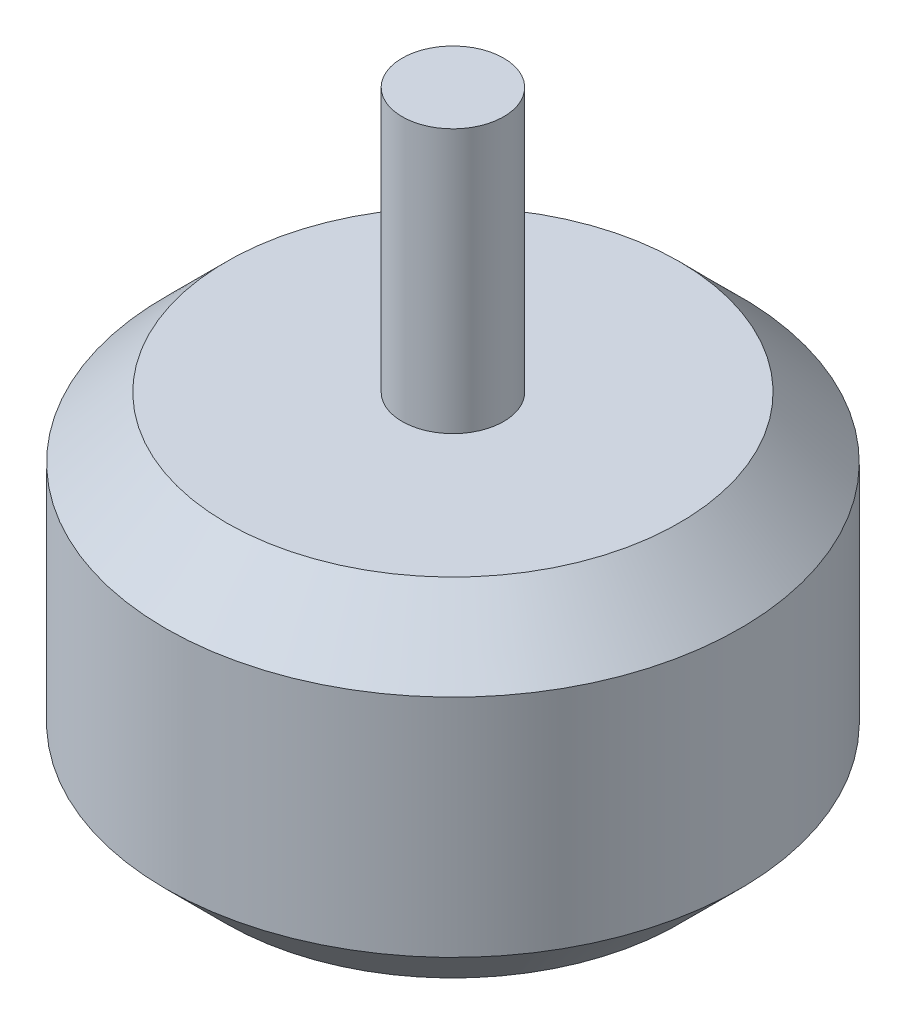
SolidWorks part; units mm, degrees
material "自定义塑料"
ref_plane "前视基准面" through (0, 0, 0) normal (0, 0, 1) x (1, 0, 0)
ref_plane "上视基准面" through (0, 0, 0) normal (0, 1, 0) x (1, 0, 0)
ref_plane "右视基准面" through (0, 0, 0) normal (1, 0, 0) x (0, 0, -1)
sketch "草图1" plane through (0, 0, 0) normal (0, 1, 0) x (1, 0, 0)
  circle A0 centre (0, 0) radius 14.15
  dimension "D1" = 28.3
extrude "凸台-拉伸1" add sketch "草图1" along normal blind 17.1
sketch "草图2" plane through (0, 17.1, 0) normal (0, 1, 0) x (1, 0, 0)
  circle A0 centre (0, 0) radius 2.5
  dimension "D1" = 5
extrude "凸台-拉伸2" add sketch "草图2" along normal blind 13
chamfer "倒角1" distance 3 angle 45 2 edges at (0, 0, 14.15) (0, 17.1, 14.15)
sketch "草图3" plane through (0, 0, 0) normal (0, -1, 0) x (1, 0, 0)
  line L0 (-1000, 0) -> (49000, 0) construction
  line L1 (0, -1000) -> (0, 49000) construction
  circle A0 centre (-8, 0) radius 1.5
  circle A1 centre (0, 8) radius 1.5
  circle A2 centre (8, 0) radius 1.5
  circle A3 centre (0, -8) radius 1.5
  dimension "D1" = 3
  dimension "D2" = 3
  dimension "D3" = 8
  dimension "D4" = 8
extrude "切除-拉伸1" cut sketch "草图3" against normal blind 4
sketch "草图4" plane through (0, 0, 0) normal (0, -1, 0) x (1, 0, 0)
  circle A0 centre (0, 0) radius 2.5
  dimension "D1" = 5
extrude "凸台-拉伸3" add sketch "草图4" along normal blind 2
